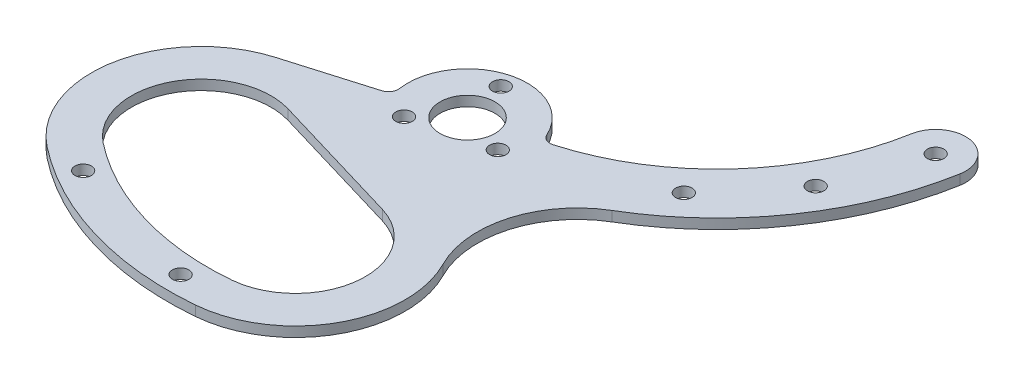
SolidWorks part; units mm, degrees
ref_plane "Спереди" through (0, 0, 0) normal (0, 0, 1) x (1, 0, 0)
ref_plane "Сверху" through (0, 0, 0) normal (0, 1, 0) x (1, 0, 0)
ref_plane "Справа" through (0, 0, 0) normal (1, 0, 0) x (0, 0, -1)
sketch "Эскиз1" plane through (0, 0, 0) normal (0, 1, 0) x (1, 0, 0)
  line L0 (0, 0) -> (-17.087, -57.5155) construction
  line L1 (0, 50) -> (53.1796, 40.623) construction
  line L2 (-27.2055, -44.3155) -> (-31.3909, -51.1333) construction
  line L3 (0, 0) -> (-6.5333, -6.19) construction
  line L4 (0, 50) -> (46.7654, 23) construction
  line L5 (-11.5083, -3.4) -> (-29.7142, -8.7788)
  line L6 (0, 0) -> (0, 50) construction
  line L12 (-19.4939, -16.457) -> (7.3467, -24.4309)
  arc A0 (5.3048, -59.765) -> (-37.075, -47.1746) centre (0, 0) cw
  arc A1 (-32.1317, -40.8846) -> (4.5975, -51.7964) centre (0, 0) ccw
  circle A2 centre (-1.5108, -55.9796) radius 1.65
  circle A3 centre (-29.2982, -47.7244) radius 1.65
  arc A4 (-29.2982, -47.7244) -> (-1.5108, -55.9796) centre (0, 0) ccw construction
  arc A5 (47.2708, 41.6649) -> (11.5083, 3.4) centre (0, 50) cw
  circle A6 centre (0, 0) radius 5.5
  arc A7 (59.0885, 39.5811) -> (30.5985, -1.6113) centre (0, 50) cw
  arc A8 (4.5975, -51.7964) -> (7.3467, -24.4309) centre (3.3597, -37.8512) ccw
  arc A9 (47.2708, 41.6649) -> (59.0885, 39.5811) centre (53.1796, 40.623) cw
  circle A10 centre (8.6273, -2.5631) radius 1.65
  circle A11 centre (-6.5333, -6.19) radius 1.65
  arc A12 (30.5985, -1.6113) -> (22.9703, -27.8799) centre (40.798, -18.8151) ccw
  circle A13 centre (0, 0) radius 9 construction
  circle A14 centre (-2.094, 8.753) radius 1.65
  arc A15 (34.7105, 8.6336) -> (53.8916, 46.5806) centre (0, 50) ccw construction
  arc A16 (5.3048, -59.765) -> (22.9703, -27.8799) centre (3.3597, -37.8512) ccw
  circle A17 centre (53.1796, 40.623) radius 1.65
  arc A18 (-32.1317, -40.8846) -> (-19.4939, -16.457) centre (-23.4809, -29.8772) cw
  circle A19 centre (46.7654, 23) radius 1.65
  circle A20 centre (34.7105, 8.6336) radius 1.65
  arc A22 (11.5083, 3.4) -> (-11.5083, -3.4) centre (0, 0) ccw
  arc A23 (-37.075, -47.1746) -> (-29.7142, -8.7788) centre (-23.4809, -29.8772) cw
  point P9 (0, 0)
  point P26 (0, 0)
  point P51 (0, 50)
  dimension "D2" = 22
  dimension "D3" = 52
  dimension "D4" = 28
  dimension "D7" = 18
  dimension "D8" = 3.3
  dimension "D9" = 11
  dimension "D10" = 3
  dimension "D11" = 50
  dimension "D12" = 48
  dimension "D13" = 60
  dimension "D14" = 80
  dimension "D20" = 56
  dimension "D17" = 12
  dimension "D18" = 20
  dimension "D19" = 3
  dimension "D21" = 30
  dimension "D5" = 15
  dimension "D6" = 60
  dimension "D15" = 20
extrude "Основа" add sketch "Эскиз1" along normal blind 2
fillet "Скругление1" radius 2 2 edges at (11.5083, 1, -3.4) (-11.5083, 1, 3.4)
